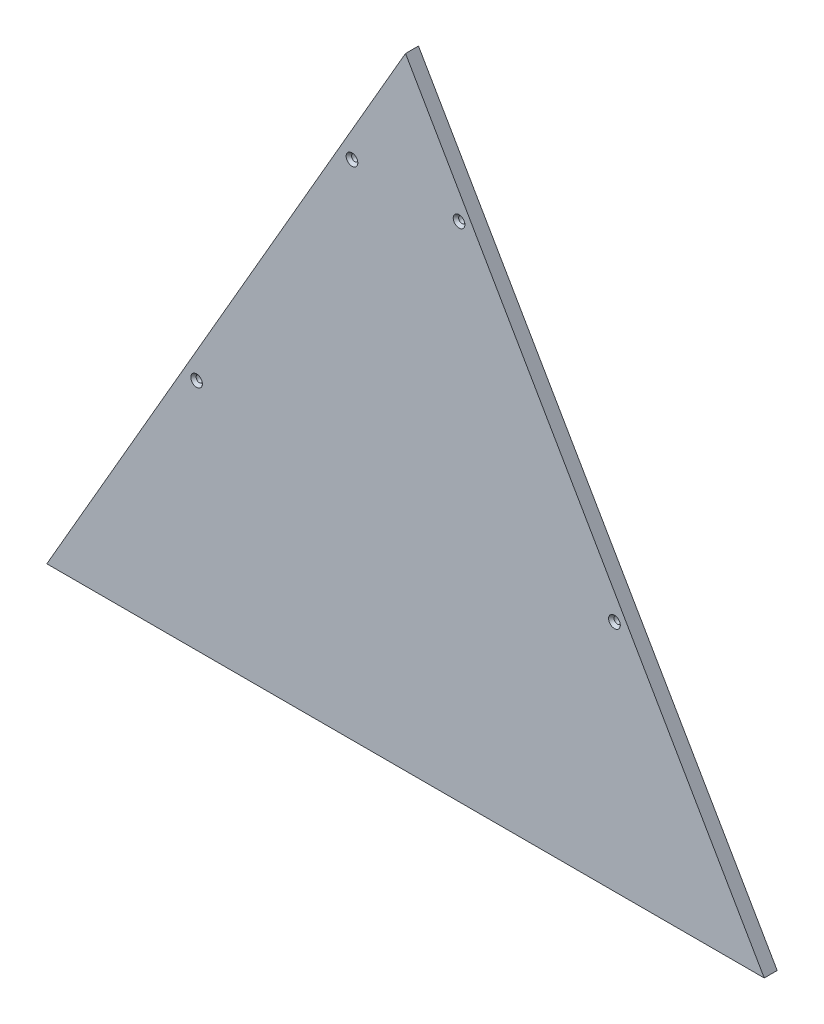
SolidWorks part; units mm, degrees
material "Acrylic (Medium-high impact)"
ref_plane "Front Plane" through (0, 0, 0) normal (0, 0, 1) x (1, 0, 0)
ref_plane "Top Plane" through (0, 0, 0) normal (0, 1, 0) x (1, 0, 0)
ref_plane "Right Plane" through (0, 0, 0) normal (1, 0, 0) x (0, 0, -1)
sketch "Sketch1" plane through (0, 0, 0) normal (0, 0, 1) x (1, 0, 0)
  line L0 (72.911, 164.3985) -> (-102.984, -140.2605)
  line L1 (-102.984, -140.2605) -> (248.806, -140.2605)
  line L2 (248.806, -140.2605) -> (72.911, 164.3985)
  dimension "D1" = 351.79
extrude "Boss-Extrude1" add sketch "Sketch1" along normal blind 6.35 contours L0 L1 L2
ref_plane "Plane1" through (89.4144, 154.8703, 0) normal (0.5, 0.866, 0) x (0, 0, 1)
sketch "Sketch3" plane through (89.4144, 154.8703, 0) normal (0.5, 0.866, 0) x (0, 0, 1)
  line L0 (6.35, -19.0565) -> (6.35, -2.277) construction
ref_plane "Plane2" through (-52.9589, 91.7275, 0) normal (0.5, -0.866, 0) x (0, 0, -1)
sketch "Sketch4" plane through (-52.9589, 91.7275, 0) normal (0.5, -0.866, 0) x (0, 0, -1)
  line L0 (-6.35, 145.342) -> (-6.35, 86.9434) construction
hole_wizard "CSK for #4 Flat Head Machine Screw1" positions "3DSketch1" profile "Sketch2" countersink size "#4" standard "ANSI Inch" end condition through all
sketch3d "3DSketch1"
  line L0 (72.911, 164.3985, 6.35) -> (-102.984, -140.2605, 6.35) construction
  line L1 (248.806, -140.2605, 6.35) -> (72.911, 164.3985, 6.35) construction
  line L2 (72.911, 164.3985, 6.35) -> (22.3363, 135.1992, 6.35) construction
  line L3 (72.911, 164.3985, 6.35) -> (87.4424, 156.0088, 6.35) construction
  point P0 (46.6602, 106.2309, 6.35)
  point P2 (-29.5398, -25.7514, 6.35)
  point P4 (99.1617, 106.2309, 6.35)
  point P6 (175.3617, -25.7514, 6.35)
  dimension "D1" = 6.35
  dimension "D2" = 6.35
  dimension "D3" = 6.35
  dimension "D4" = 6.35
  dimension "D5" = 63.5
  dimension "D6" = 63.5
  dimension "D7" = 215.9
  dimension "D8" = 215.9
sketch "Sketch2" plane through (46.6602, 106.2309, 6.35) normal (1, 0, 0) x (0, -1, 0)
  line L0 (0, 0) -> (0, 6.35)
  line L1 (0, 6.35) -> (1.6319, 6.35)
  line L2 (1.6319, 6.35) -> (1.6319, 1.4098)
  line L3 (1.6319, 1.4098) -> (2.8575, 0)
  line L5 (2.8575, 0) -> (0, 0)
  line L6 (-1.6319, 1.4098) -> (-2.8575, 0) construction
  line L11 (0, -6.35) -> (0, 107.95) construction
  dimension "Thru Hole Dia." = 3.2639
  dimension "Thru Hole Depth" = 6.35
  dimension "Near C'Sink Dia." = 5.715
  dimension "Near C'Sink Angle" = 82
fillet "Fillet1" [suppressed] radius 12.7
